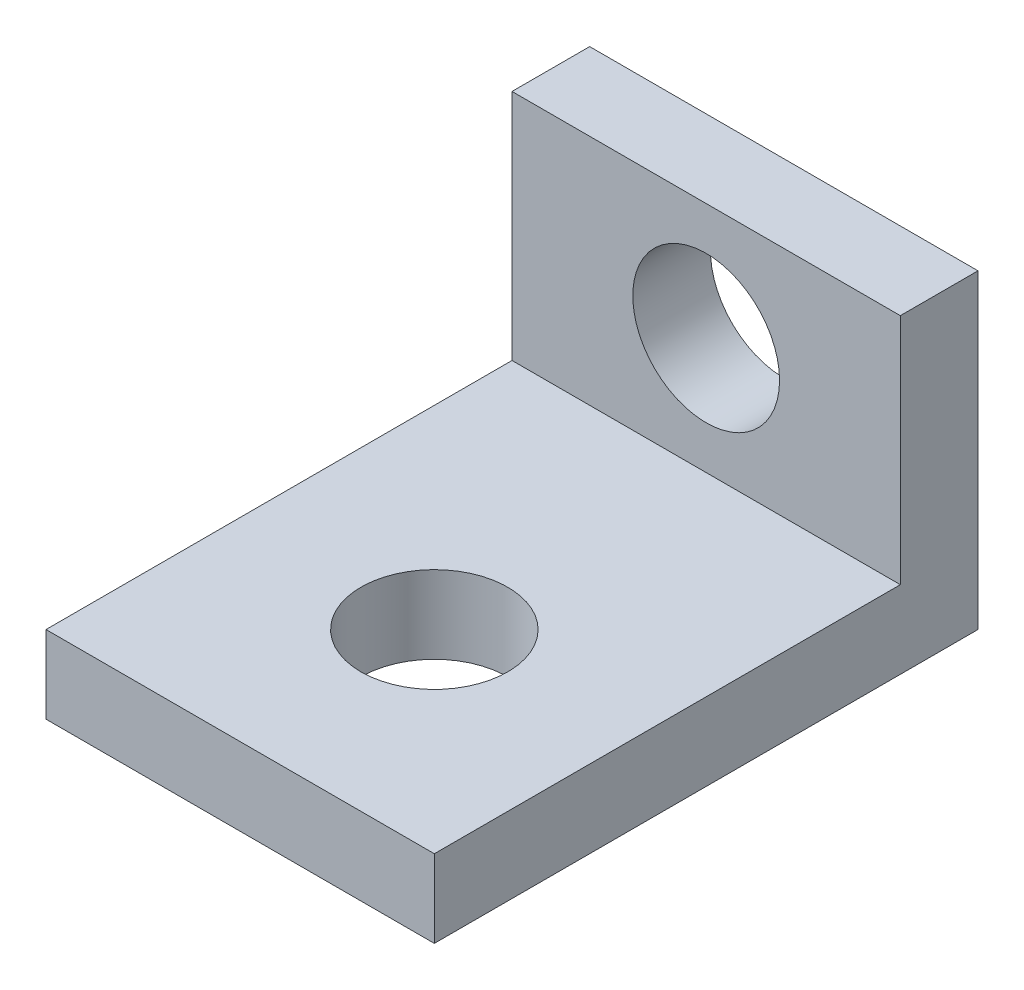
SolidWorks part; units mm, degrees
ref_plane "Front Plane" through (0, 0, 0) normal (0, 0, 1) x (1, 0, 0)
ref_plane "Top Plane" through (0, 0, 0) normal (0, 1, 0) x (1, 0, 0)
ref_plane "Right Plane" through (0, 0, 0) normal (1, 0, 0) x (0, 0, -1)
sketch "Sketch2" plane through (0, 0, 0) normal (1, 0, 0) x (0, 0, -1)
  line L1 (0, 0) -> (10.16, 0)
  line L2 (0, 0) -> (0, 10.16)
  line L3 (0, 10.16) -> (10.16, 10.16)
  line L4 (10.16, 0) -> (10.16, 10.16)
  line L5 (5.08, 10.16) -> (5.08, 0) construction
  line L6 (0, 5.08) -> (10.16, 5.08) construction
  point P204 (5.08, 5.08)
  dimension "D1" = 10.16
extrude "Boss-Extrude1" add sketch "Sketch2" along normal blind 38.1
sketch "Sketch3" plane through (38.1, 0, 0) normal (1, 0, 0) x (0, 0, -1)
  line L0 (10.16, 0) -> (10.16, 10.16) construction
  line L1 (0, 10.16) -> (7.62, 10.16)
  line L2 (0, 10.16) -> (0, 2.54)
  line L3 (0, 2.54) -> (7.62, 2.54)
  line L4 (7.62, 10.16) -> (7.62, 2.54)
  line L5 (3.81, 2.54) -> (3.81, 10.16) construction
  line L6 (0, 6.35) -> (7.62, 6.35) construction
  point P556 (3.81, 6.35)
  dimension "D1" = 2.54
extrude "Cut-Extrude1" cut sketch "Sketch3" against normal up to surface (38.1 mm away) and the other way through all up to face at (0, 5.08, -5.08)
sketch "Sketch7" plane through (0, 0, -7.62) normal (0, 0, 1) x (1, 0, 0)
  line L0 (0, 6.35) -> (38.1, 6.35) construction
  line L1 (0, 2.54) -> (0, 10.16) construction
  line L2 (38.1, 10.16) -> (38.1, 2.54) construction
  line L3 (38.1, 0) -> (0, 0) construction
  line L4 (6.35, 10.16) -> (6.35, 2.54) construction
  line L5 (0, 10.16) -> (38.1, 10.16) construction
  line L6 (0, 2.54) -> (38.1, 2.54) construction
  line L7 (19.05, 10.16) -> (19.05, 2.54) construction
  line L8 (31.75, 10.16) -> (31.75, 2.54) construction
  line L9 (0, 2.54) -> (38.1, 2.54) construction
  dimension "D1" = 6.35
  dimension "D2" = 6.35
hole_wizard "M4 Clearance Hole2" positions "Sketch10" profile "Sketch11" hole size "M4" standard "ANSI Metric" end condition through all
sketch "Sketch10" plane through (0, 0, -7.62) normal (0, 0, 1) x (1, 0, 0)
  line L0 (6.35, 10.16) -> (6.35, 2.54) construction
  line L1 (31.75, 10.16) -> (31.75, 2.54) construction
  point P0 (6.35, 6.35)
  point P4 (31.75, 6.35)
sketch "Sketch11" plane through (6.35, 6.35, -7.62) normal (1, 0, 0) x (0, -1, 0)
  line L0 (0, 0) -> (0, 2.54)
  line L1 (0, 2.54) -> (2.4, 2.54)
  line L2 (2.4, 2.54) -> (2.4, 0)
  line L5 (2.4, 0) -> (0, 0)
  line L11 (0, -6.35) -> (0, 107.95) construction
  dimension "Thru Hole Dia." = 4.8
  dimension "Thru Hole Depth" = 2.54
sketch "Sketch13" plane through (0, 0, 0) normal (0, 0, 1) x (1, 0, 0)
  line L1 (0, 2.54) -> (38.1, 2.54)
  line L2 (0, 2.54) -> (0, 0)
  line L3 (0, 0) -> (38.1, 0)
  line L4 (38.1, 2.54) -> (38.1, 0)
  line L5 (19.05, 0) -> (19.05, 2.54) construction
  line L6 (0, 1.27) -> (38.1, 1.27) construction
  point P300 (19.05, 1.27)
extrude "Boss-Extrude2" add sketch "Sketch13" along normal blind 7.62
sketch "Sketch14" plane through (0, 2.54, 0) normal (0, 1, 0) x (1, 0, 0)
  line L0 (0, -1.27) -> (38.1, -1.27) construction
  line L3 (0, -7.62) -> (0, 7.62) construction
  line L4 (38.1, 7.62) -> (38.1, -7.62) construction
  line L5 (38.1, -7.62) -> (0, -7.62) construction
  line L6 (6.35, 7.62) -> (6.35, -7.62) construction
  line L7 (31.75, 7.62) -> (31.75, -7.62) construction
  dimension "D1" = 6.35
hole_wizard "M4 Clearance Hole3" positions "Sketch15" profile "Sketch16" hole size "M4" standard "ANSI Metric" end condition through all
sketch "Sketch15" plane through (0, 2.54, 0) normal (0, 1, 0) x (1, 0, 0)
  line L0 (0, -1.27) -> (38.1, -1.27) construction
  line L1 (6.35, 7.62) -> (6.35, -7.62) construction
  line L2 (31.75, 7.62) -> (31.75, -7.62) construction
  point P0 (6.35, -1.27)
  point P6 (31.75, -1.27)
sketch "Sketch16" plane through (6.35, 2.54, 1.27) normal (1, 0, 0) x (0, 0, 1)
  line L0 (0, 0) -> (0, 2.54)
  line L1 (0, 2.54) -> (2.4, 2.54)
  line L2 (2.4, 2.54) -> (2.4, 0)
  line L5 (2.4, 0) -> (0, 0)
  line L11 (0, -6.35) -> (0, 107.95) construction
  dimension "Thru Hole Dia." = 4.8
  dimension "Thru Hole Depth" = 2.54
sketch "Sketch17" plane through (0, 0, -10.16) normal (0, 0, -1) x (-1, 0, 0)
  line L0 (-38.1, 0) -> (0, 0) construction
  line L1 (-38.1, 10.16) -> (-12.7, 10.16)
  line L2 (-38.1, 10.16) -> (-38.1, 0)
  line L3 (-38.1, 0) -> (-12.7, 0)
  line L4 (-12.7, 10.16) -> (-12.7, 0)
  line L5 (-25.4, 0) -> (-25.4, 10.16) construction
  line L6 (-38.1, 5.08) -> (-12.7, 5.08) construction
  circle A0 centre (-6.35, 6.35) radius 2.4 construction
  point P236 (-25.4, 5.08)
  dimension "D1" = 6.35
extrude "Cut-Extrude2" cut sketch "Sketch17" against normal up to surface (17.78 mm away) up to face at (19.05, 1.27, 7.62)
